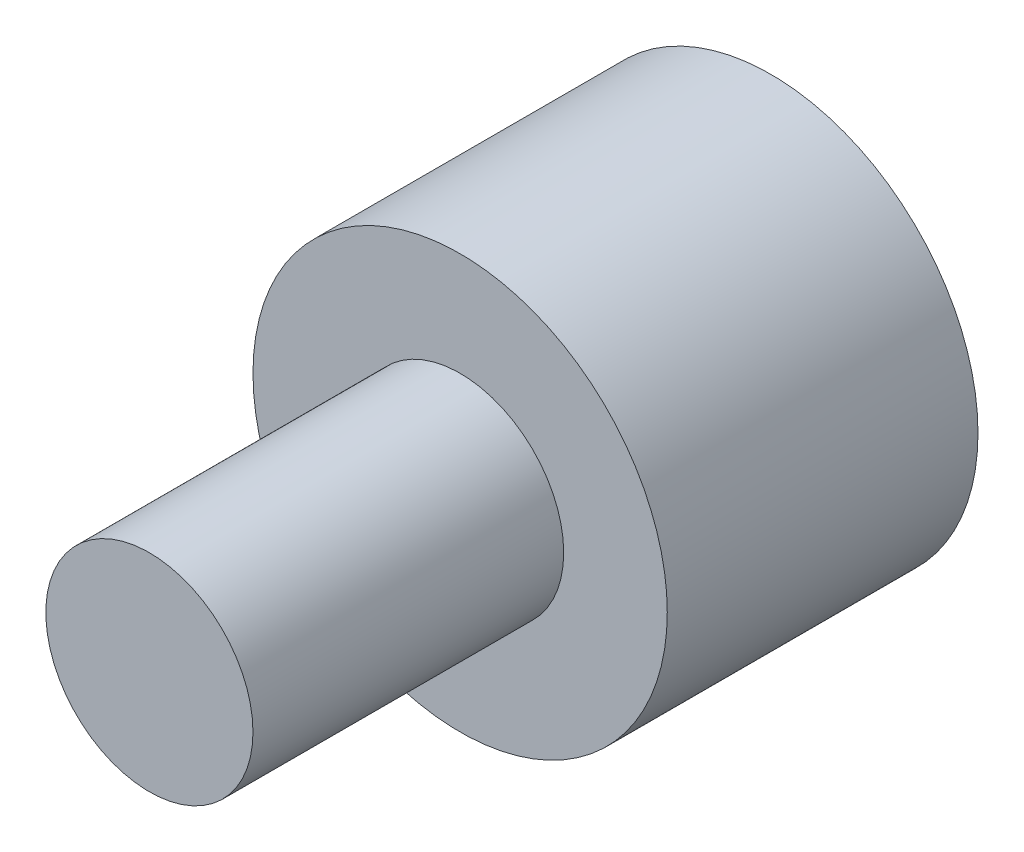
SolidWorks part; units mm, degrees
ref_plane "Front Plane" through (0, 0, 0) normal (0, 0, 1) x (1, 0, 0)
ref_plane "Top Plane" through (0, 0, 0) normal (0, 1, 0) x (1, 0, 0)
ref_plane "Right Plane" through (0, 0, 0) normal (1, 0, 0) x (0, 0, -1)
sketch "Sketch1" plane through (0, 0, 0) normal (0, 0, 1) x (1, 0, 0)
  circle A0 centre (0, 0) radius 20
extrude "Boss-Extrude1" add sketch "Sketch1" along normal blind 30
sketch "Sketch2" plane through (0, 0, 30) normal (0, 0, 1) x (1, 0, 0)
  circle A0 centre (0, 0) radius 10
extrude "Boss-Extrude2" add sketch "Sketch2" along normal blind 30
